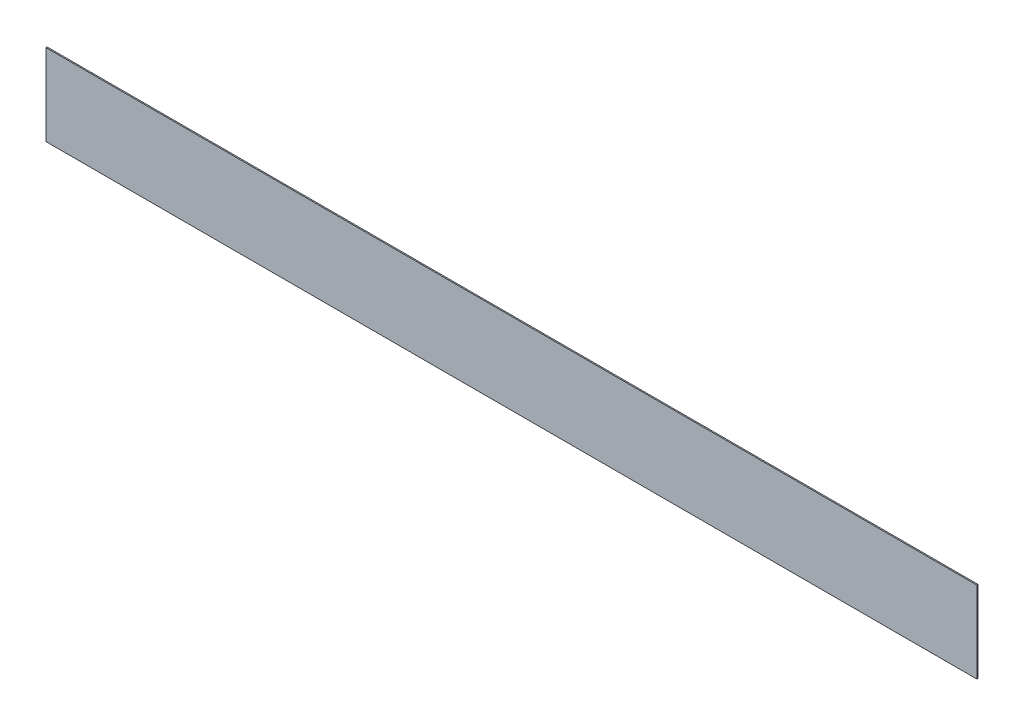
SolidWorks part; units mm, degrees
ref_plane "前视基准面" through (0, 0, 0) normal (0, 0, 1) x (1, 0, 0)
ref_plane "上视基准面" through (0, 0, 0) normal (0, 1, 0) x (1, 0, 0)
ref_plane "右视基准面" through (0, 0, 0) normal (1, 0, 0) x (0, 0, -1)
other "Configuration Table"
sketch "草图1" plane through (0, 0, 0) normal (0, 0, 1) x (1, 0, 0)
  line L1 (-4000, -350) -> (4000, -350)
  line L2 (-4000, -350) -> (-4000, 350)
  line L3 (-4000, 350) -> (4000, 350)
  line L4 (4000, -350) -> (4000, 350)
  line L5 (-4000, -350) -> (4000, 350) construction
  line L6 (-4000, 350) -> (4000, -350) construction
  point P0 (0, 0)
  dimension "D1" = 8000
  dimension "D2" = 700
extrude "凸台-拉伸1" add sketch "草图1" along normal blind 10
